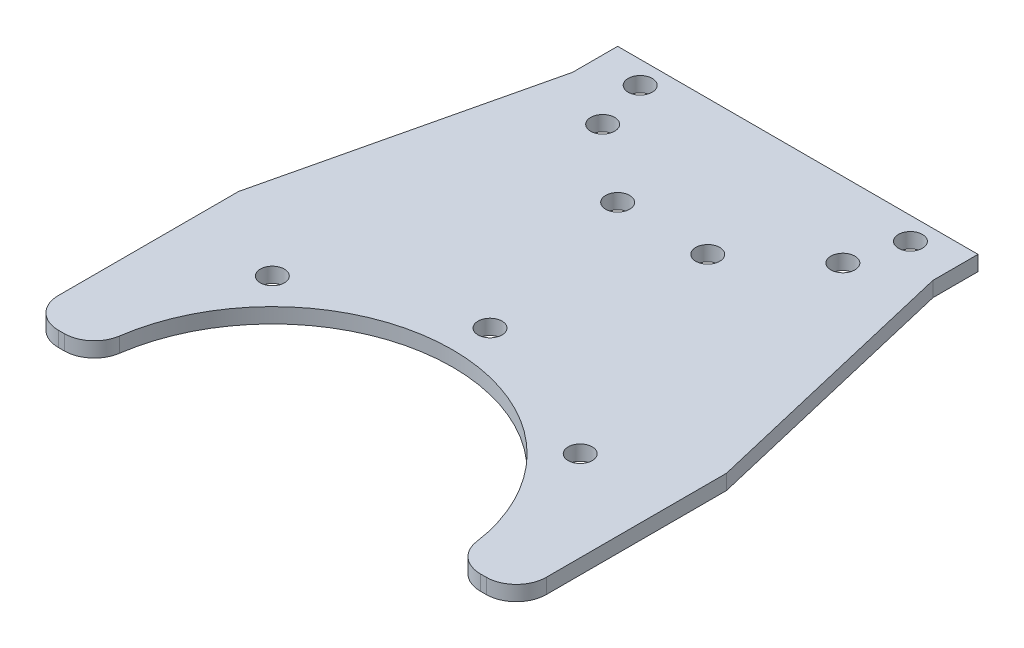
SolidWorks part; units mm, degrees
ref_plane "前视基准面" through (0, 0, 0) normal (0, 0, 1) x (1, 0, 0)
ref_plane "上视基准面" through (0, 0, 0) normal (0, 1, 0) x (1, 0, 0)
ref_plane "右视基准面" through (0, 0, 0) normal (1, 0, 0) x (0, 0, -1)
sketch "草图1" plane through (0, 0, 0) normal (0, 1, 0) x (1, 0, 0)
  line L0 (0, 0) -> (0, 32) construction
  line L1 (-32.5, -32) -> (32.5, -32)
  line L2 (-32.5, -32) -> (-32.5, 32)
  line L3 (-32.5, 32) -> (32.5, 32)
  line L4 (32.5, -32) -> (32.5, 32)
  line L5 (-32.5, -32) -> (32.5, 32) construction
  line L6 (-32.5, 32) -> (32.5, -32) construction
  line L7 (24, 32) -> (-24, 32)
  line L8 (24, 32) -> (24, 38)
  line L9 (24, 38) -> (-24, 38)
  line L10 (-24, 32) -> (-24, 38)
  line L11 (-18, 35) -> (-24, 35) construction
  line L25 (0, -32) -> (-20.5061, -11.4939) construction
  circle A0 centre (-16, 28) radius 1.6
  circle A1 centre (16, 28) radius 1.6
  circle A2 centre (18, 35) radius 1.6
  circle A3 centre (-18, 35) radius 1.6
  circle A8 centre (0, -32) radius 24
  circle A9 centre (-20.5061, -11.4939) radius 1.6
  circle A10 centre (0, -3) radius 1.6
  circle A11 centre (20.5061, -11.4939) radius 1.6
  circle A12 centre (-6, 20) radius 1.6
  circle A13 centre (6, 20) radius 1.6
  point P0 (0, 0)
  dimension "D3" = 3.2
  dimension "D6" = 3.2
  dimension "D8" = 12
  dimension "D16" = 48
  dimension "D18" = 3.2
  dimension "D9" = 3.2
  dimension "D1" = 48
  dimension "D2" = 6
  dimension "D4" = 32
  dimension "D5" = 4
  dimension "D7" = 36
  dimension "D10" = 12
  dimension "D14" = 64
  dimension "D15" = 65
  dimension "D17" = 29
  dimension "D20" = 45
  dimension "D19" = 3
extrude "凸台-拉伸1" add sketch "草图1" along normal mid plane 2 contours L10 L3 L8 L9 | L1 L4 L3 L2
fillet "圆角2" radius 4 4 edges at (32.5, 0, 32) (24, 0, 32) (-24, 0, 32) (-32.5, 0, 32)
sketch "草图2" plane through (0, 1, 0) normal (0, 1, 0) x (1, 0, 0)
  line L0 (0, 0) -> (0, 51.2357) construction
  line L1 (32.5, 32) -> (24, 32)
  line L2 (24, 32) -> (32.5, -4)
  line L4 (32.5, -4) -> (32.5, 32)
  line L5 (-32.5, -4) -> (-32.5, 32)
  line L6 (-24, 32) -> (-32.5, -4)
  line L7 (-32.5, 32) -> (-24, 32)
  line L8 (32.5, -28) -> (32.5, 32) construction
  dimension "D1" = 36
extrude "切除-拉伸1" cut sketch "草图2" against normal through all and the other way through all
